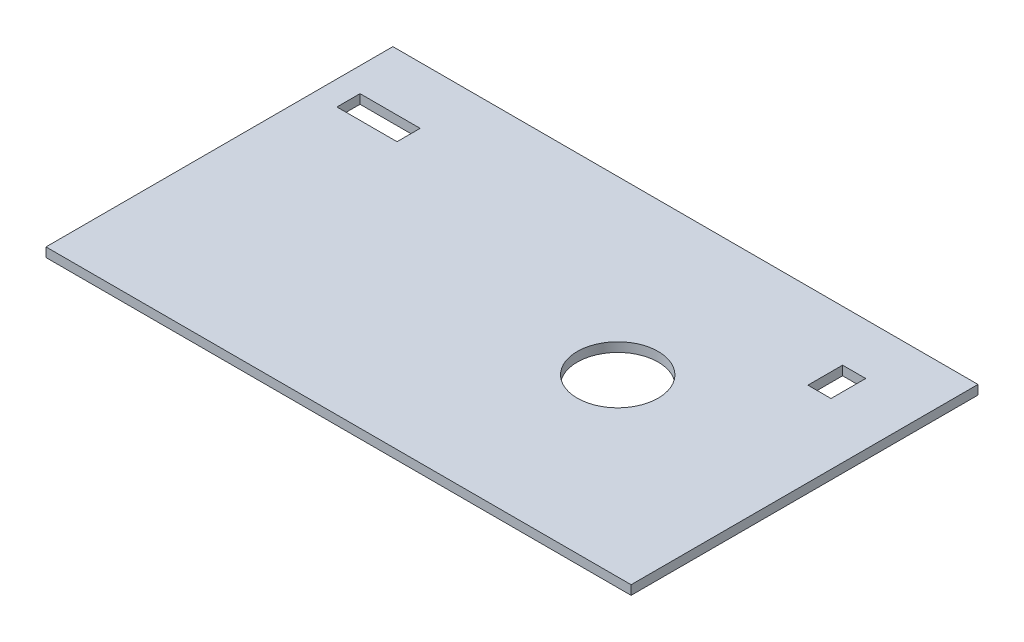
SolidWorks part; units mm, degrees
ref_plane "Front Plane" through (0, 0, 0) normal (0, 0, 1) x (1, 0, 0)
ref_plane "Top Plane" through (0, 0, 0) normal (0, 1, 0) x (1, 0, 0)
ref_plane "Right Plane" through (0, 0, 0) normal (1, 0, 0) x (0, 0, -1)
sketch "Sketch2" plane through (0, 0, 0) normal (0, 1, 0) x (1, 0, 0)
  line L1 (126.5, 75) -> (-126.5, 75)
  line L2 (126.5, 75) -> (126.5, -75)
  line L3 (126.5, -75) -> (-126.5, -75)
  line L4 (-126.5, 75) -> (-126.5, -75)
  line L5 (126.5, 75) -> (-126.5, -75) construction
  line L6 (126.5, -75) -> (-126.5, 75) construction
  point P0 (0, 0)
  dimension "D1" = 253
  dimension "D2" = 150
extrude "Boss-Extrude1" add sketch "Sketch2" along normal blind 4
sketch "Sketch3" plane through (0, 4, 0) normal (0, 1, 0) x (1, 0, 0)
  line L1 (-90, 50.2881) -> (-116, 50.2881)
  line L2 (-90, 50.2881) -> (-90, 40.2881)
  line L3 (-90, 40.2881) -> (-116, 40.2881)
  line L4 (-116, 50.2881) -> (-116, 40.2881)
  line L5 (-90, 50.2881) -> (-116, 40.2881) construction
  line L6 (-90, 40.2881) -> (-116, 50.2881) construction
  line L8 (100, 52.9454) -> (90, 52.9454)
  line L9 (100, 52.9454) -> (100, 37.9454)
  line L10 (100, 37.9454) -> (90, 37.9454)
  line L11 (90, 52.9454) -> (90, 37.9454)
  line L12 (100, 52.9454) -> (90, 37.9454) construction
  line L13 (100, 37.9454) -> (90, 52.9454) construction
  circle A0 centre (45, 0.7132) radius 17.5
  point P0 (-103, 45.2881)
  point P5 (95, 45.4454)
  dimension "D5" = 35
  dimension "D1" = 26
  dimension "D2" = 10
  dimension "D3" = 15
  dimension "D4" = 10
  dimension "D6" = 45
  dimension "D7" = 90
  dimension "D8" = 90
extrude "Cut-Extrude1" cut sketch "Sketch3" against normal through all
